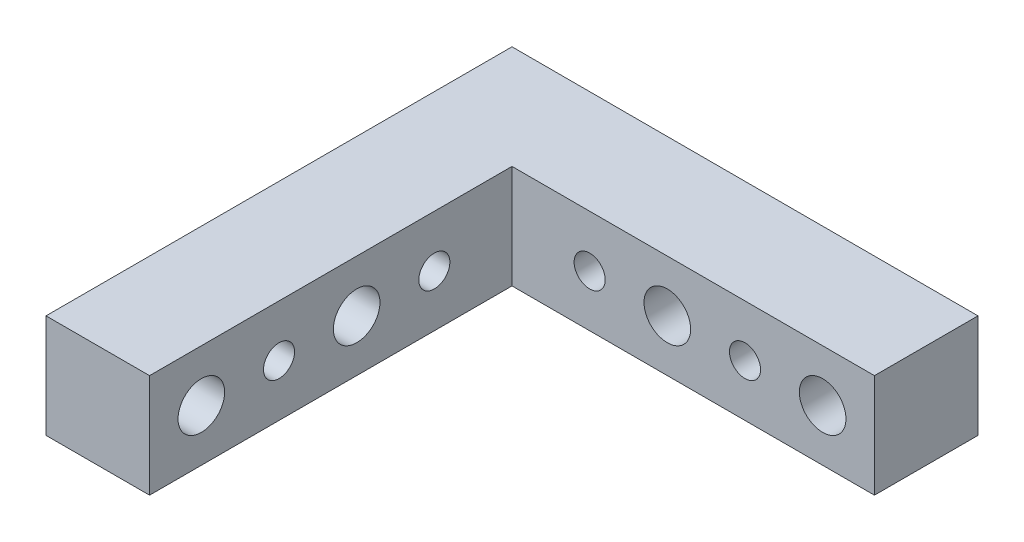
SolidWorks part; units mm, degrees
ref_plane "前视基准面" through (0, 0, 0) normal (0, 0, 1) x (1, 0, 0)
ref_plane "上视基准面" through (0, 0, 0) normal (0, 1, 0) x (1, 0, 0)
ref_plane "右视基准面" through (0, 0, 0) normal (1, 0, 0) x (0, 0, -1)
sketch "草图1" plane through (0, 0, 0) normal (0, 1, 0) x (1, 0, 0)
  line L0 (0, 0) -> (0, -90)
  line L1 (0, -90) -> (20, -90)
  line L2 (20, -90) -> (20, -20)
  line L3 (20, -20) -> (90, -20)
  line L4 (90, -20) -> (90, 0)
  line L5 (90, 0) -> (0, 0)
  dimension "D1" = 90
  dimension "D2" = 90
  dimension "D3" = 20
  dimension "D4" = 20
extrude "凸台-拉伸1" add sketch "草图1" along normal blind 20
sketch "草图2" plane through (0, 0, 0) normal (-1, 0, 0) x (0, 0, 1)
  line L0 (0, 20) -> (0, 0) construction
  line L1 (90, 20) -> (90, 0) construction
  circle A0 centre (35, 10) radius 3
  circle A1 centre (50, 10) radius 4.5
  circle A2 centre (65, 10) radius 3
  circle A3 centre (80, 10) radius 4.5
  point P10 (0, 0)
  point P13 (90, 10)
  dimension "D1" = 6
  dimension "D2" = 9
  dimension "D3" = 6
  dimension "D4" = 9
  dimension "D5" = 35
  dimension "D6" = 15
  dimension "D7" = 15
  dimension "D8" = 15
extrude "切除-拉伸1" cut sketch "草图2" against normal blind 20
sketch "草图3" plane through (0, 0, 0) normal (0, 0, -1) x (-1, 0, 0)
  line L0 (0, 20) -> (0, 0) construction
  circle A0 centre (-35, 10) radius 3
  circle A1 centre (-50, 10) radius 4.5
  circle A2 centre (-65, 10) radius 3
  circle A3 centre (-80, 10) radius 4.5
  point P10 (-63.8651, 8.6477)
  point P11 (0, 0)
  point P12 (0, 0)
  point P13 (0, 10)
  dimension "D1" = 6
  dimension "D2" = 6
  dimension "D3" = 9
  dimension "D4" = 9
  dimension "D5" = 35
  dimension "D6" = 15
  dimension "D7" = 15
  dimension "D8" = 15
extrude "切除-拉伸2" cut sketch "草图3" against normal blind 20
